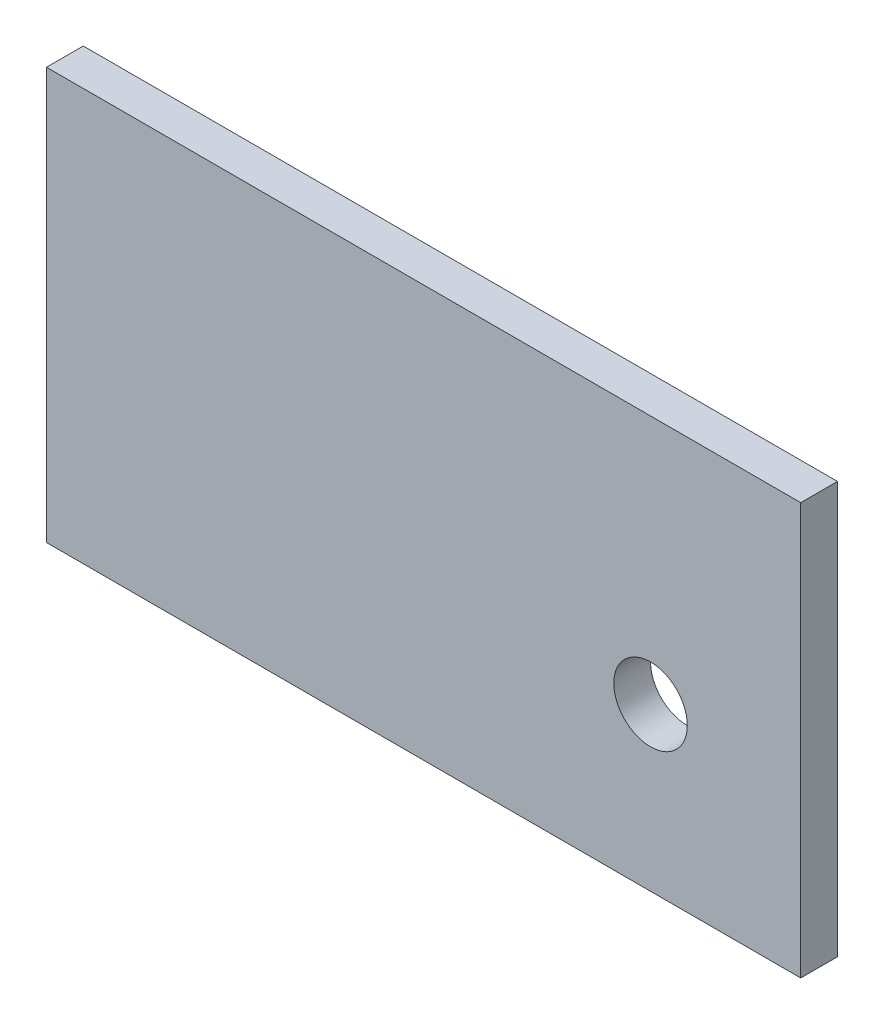
SolidWorks part; units mm, degrees
ref_plane "Front Plane" through (0, 0, 0) normal (0, 0, 1) x (1, 0, 0)
ref_plane "Top Plane" through (0, 0, 0) normal (0, 1, 0) x (1, 0, 0)
ref_plane "Right Plane" through (0, 0, 0) normal (1, 0, 0) x (0, 0, -1)
sketch "Sketch1" plane through (0, 0, 0) normal (0, 0, 1) x (1, 0, 0)
  line L1 (0, 0) -> (65.151, 0)
  line L2 (0, 0) -> (0, 35.56)
  line L3 (0, 35.56) -> (65.151, 35.56)
  line L4 (65.151, 0) -> (65.151, 35.56)
  circle A0 centre (52.1758, 13.9835) radius 3.175
  dimension "D3" = 6.35
  dimension "D1" = 65.151
  dimension "D2" = 35.56
  dimension "D4" = 21.5765
  dimension "D5" = 52.1758
extrude "Boss-Extrude1" add sketch "Sketch1" along normal blind 3.175
